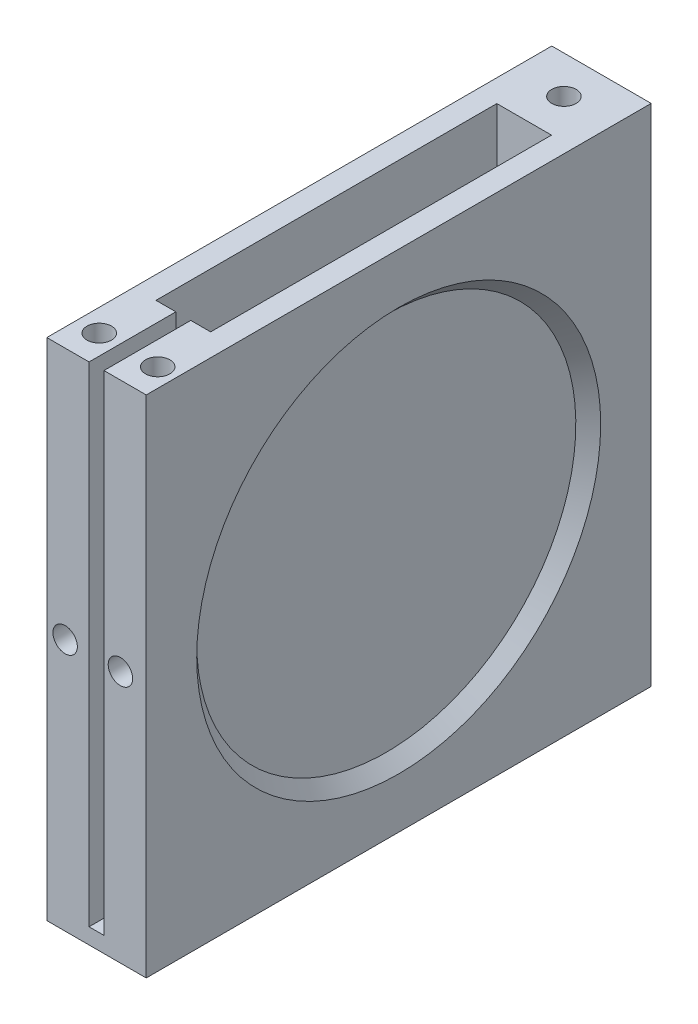
SolidWorks part; units mm, degrees
ref_plane "Front Plane" through (0, 0, 0) normal (0, 0, 1) x (1, 0, 0)
ref_plane "Top Plane" through (0, 0, 0) normal (0, 1, 0) x (1, 0, 0)
ref_plane "Right Plane" through (0, 0, 0) normal (1, 0, 0) x (0, 0, -1)
sketch "Sketch1" plane through (0, 0, 0) normal (0, 0, 1) x (1, 0, 0)
  line L1 (-10, 50.8) -> (10, 50.8)
  line L2 (-10, 50.8) -> (-10, -50.8)
  line L3 (-10, -50.8) -> (10, -50.8)
  line L4 (10, 50.8) -> (10, -50.8)
  dimension "D1" = 10
  dimension "D2" = 50.8
  dimension "D3" = 101.6
  dimension "D4" = 20
extrude "Boss-Extrude1" add sketch "Sketch1" against normal blind 101.6
ref_plane "Plane1" through (0, 0, -50.8) normal (0, 0, 1) x (1, 0, 0)
sketch "Sketch3" plane through (0, 50.8, 0) normal (0, 1, 0) x (1, 0, 0)
  line L0 (10, 0) -> (-10, 0) construction
  line L1 (-5.5, 86.0425) -> (5.5, 86.0425)
  line L2 (-5.5, 86.0425) -> (-5.5, 17.4625)
  line L3 (-5.5, 17.4625) -> (5.5, 17.4625)
  line L4 (5.5, 86.0425) -> (5.5, 17.4625)
  dimension "D1" = 11
  dimension "D2" = 68.58
  dimension "D3" = 17.4625
  dimension "D4" = 5.5
extrude "Cut-Extrude1" cut sketch "Sketch3" against normal blind 98.425
sketch "Sketch4" plane through (0, 0, 0) normal (0, 0, 1) x (1, 0, 0)
  line L0 (10, 50.8) -> (-10, 50.8) construction
  line L1 (-1.5, 50.8) -> (1.5, 50.8)
  line L2 (-1.5, 50.8) -> (-1.5, -47.625)
  line L3 (-1.5, -47.625) -> (1.5, -47.625)
  line L4 (1.5, 50.8) -> (1.5, -47.625)
  dimension "D1" = 3
  dimension "D2" = 98.425
  dimension "D3" = 1.5
extrude "Cut-Extrude2" cut sketch "Sketch4" against normal up to next
sketch "Sketch5" plane through (10, 0, 0) normal (1, 0, 0) x (0, 0, -1)
  line L0 (101.6, 50.8) -> (0, 50.8) construction
  circle A0 centre (50.8, 0) radius 40.64
  dimension "D1" = 81.28
  dimension "D2" = 50.8
  dimension "D3" = 50.8
extrude "Cut-Extrude3" cut sketch "Sketch5" against normal blind 2.5 draft 45
sketch "Sketch6" plane through (-10, 0, 0) normal (-1, 0, 0) x (0, 0, 1)
  line L0 (-101.6, 50.8) -> (0, 50.8) construction
  line L1 (0, 50.8) -> (0, -50.8) construction
  circle A0 centre (-50.8, 0) radius 40.64
  dimension "D1" = 81.28
  dimension "D2" = 50.8
  dimension "D3" = 50.8
extrude "Cut-Extrude4" cut sketch "Sketch6" against normal blind 2.5 draft 45
hole_wizard "#10 (0.1935) Diameter Hole1" positions "Sketch8" profile "Sketch7" hole size "#10" standard "ANSI Inch"
sketch "Sketch8" plane through (0, 50.8, 0) normal (0, 1, 0) x (1, 0, 0)
  point P0 (-5.4944, 6.0468)
  point P2 (6.2627, 6.0468)
  point P4 (0, 94.039)
sketch "Sketch7" plane through (-5.4944, 50.8, -6.0468) normal (1, 0, 0) x (0, 0, 1)
  line L0 (0, 0) -> (0, 9.0966)
  line L1 (0, 9.0966) -> (2.4574, 7.62)
  line L2 (2.4574, 7.62) -> (2.4574, 0)
  line L5 (2.4574, 0) -> (0, 0)
  line L10 (0, 9.0966) -> (-2.4574, 7.62) construction
  line L11 (0, -6.35) -> (0, 107.95) construction
  dimension "Hole Dia." = 4.9149
  dimension "Hole Depth" = 7.62
  dimension "Drill Angle" = 118
sketch "Sketch9" plane through (0, 0, -101.6) normal (0, 0, -1) x (-1, 0, 0)
  circle A0 centre (0, 0) radius 1.5
  dimension "D1" = 3
extrude "Cut-Extrude5" cut sketch "Sketch9" against normal up to next
hole_wizard "#10 (0.1935) Diameter Hole2" positions "Sketch11" profile "Sketch10" hole size "#10" standard "ANSI Inch"
sketch "Sketch11" plane through (0, 0, 0) normal (0, 0, 1) x (1, 0, 0)
  point P0 (4.8095, 0)
  point P2 (-6.3126, 0)
sketch "Sketch10" plane through (4.8095, 0, 0) normal (1, 0, 0) x (0, -1, 0)
  line L0 (0, 0) -> (0, 7.8266)
  line L1 (0, 7.8266) -> (2.4574, 6.35)
  line L2 (2.4574, 6.35) -> (2.4574, 0)
  line L5 (2.4574, 0) -> (0, 0)
  line L10 (0, 7.8266) -> (-2.4575, 6.35) construction
  line L11 (0, -6.35) -> (0, 107.95) construction
  dimension "Hole Dia." = 4.9149
  dimension "Hole Depth" = 6.35
  dimension "Drill Angle" = 118
hole_wizard "#10 (0.1935) Diameter Hole3" positions "Sketch13" profile "Sketch12" hole size "#10" standard "ANSI Inch"
sketch "Sketch13" plane through (0, 0, -101.6) normal (0, 0, -1) x (-1, 0, 0)
  point P0 (6.1033, 0)
  point P2 (-5.0688, 0)
sketch "Sketch12" plane through (-6.1033, 0, -101.6) normal (1, 0, 0) x (0, 1, 0)
  line L0 (0, 0) -> (0, 7.8266)
  line L1 (0, 7.8266) -> (2.4574, 6.35)
  line L2 (2.4574, 6.35) -> (2.4574, 0)
  line L5 (2.4574, 0) -> (0, 0)
  line L10 (0, 7.8266) -> (-2.4574, 6.35) construction
  line L11 (0, -6.35) -> (0, 107.95) construction
  dimension "Hole Dia." = 4.9149
  dimension "Hole Depth" = 6.35
  dimension "Drill Angle" = 118
